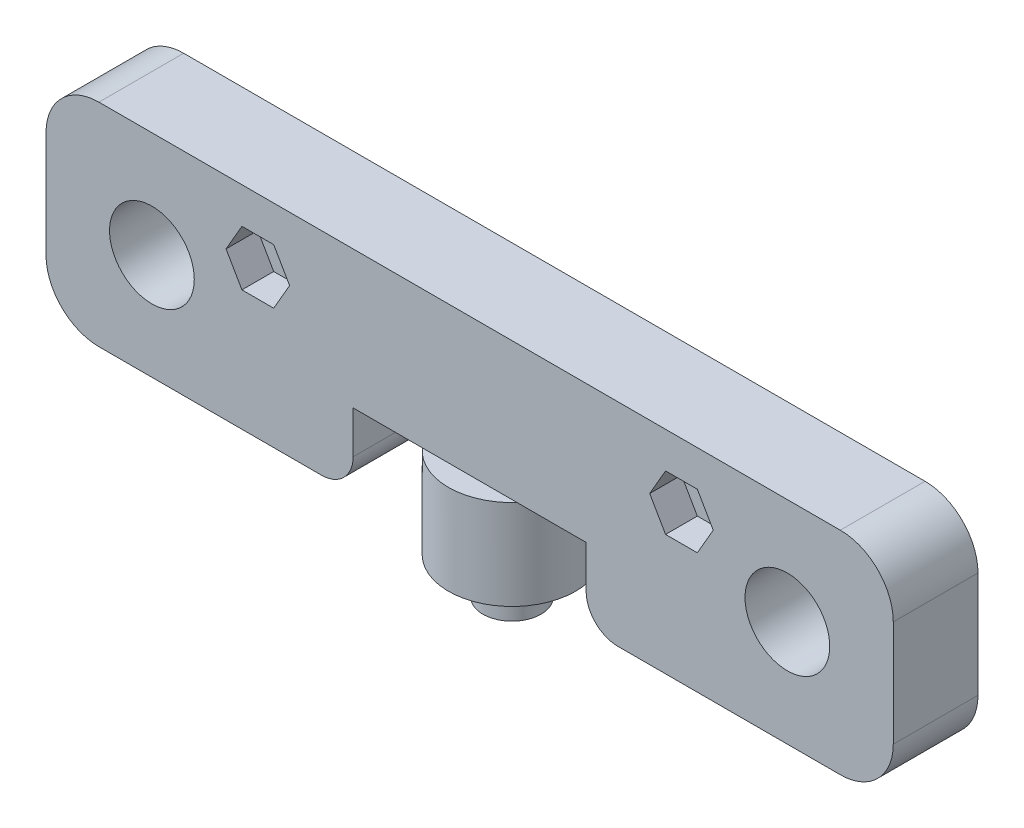
SolidWorks part; units mm, degrees
ref_plane "Front Plane" through (0, 0, 0) normal (0, 0, 1) x (1, 0, 0)
ref_plane "Top Plane" through (0, 0, 0) normal (0, 1, 0) x (1, 0, 0)
ref_plane "Right Plane" through (0, 0, 0) normal (1, 0, 0) x (0, 0, -1)
sketch "Sketch1" plane through (0, 0, 0) normal (0, 0, 1) x (1, 0, 0)
  line L0 (-11, -3) -> (-11, -10)
  line L1 (-11, -10) -> (-40, -10)
  line L2 (-40, -10) -> (-40, 10)
  line L3 (0, -12.103) -> (0, 12.103) construction
  line L4 (40, -10) -> (40, 10)
  line L5 (11, -10) -> (40, -10)
  line L6 (11, -3) -> (11, -10)
  line L7 (-11, -3) -> (11, -3)
  line L8 (-40, 10) -> (40, 10)
  circle A0 centre (-30, 0) radius 4
  circle A1 centre (-20, 4) radius 1.4
  circle A2 centre (20, 4) radius 1.4
  circle A3 centre (30, 0) radius 4
  dimension "D1" = 2.8
  dimension "D2" = 8
  dimension "D3" = 20
  dimension "D4" = 7
  dimension "D5" = 80
  dimension "D6" = 60
  dimension "D7" = 40
  dimension "D8" = 14
  dimension "D9" = 10
  dimension "D10" = 22
extrude "Boss-Extrude1" add sketch "Sketch1" along normal blind 8
fillet "outside curves" radius 5 4 edges at (40, -10, 4) (40, 10, 4) (-40, -10, 4) (-40, 10, 4)
fillet "inside curves" radius 3 2 edges at (11, -10, 4) (-11, -10, 4)
sketch "Sketch2" plane through (0, 0, 8) normal (0, 0, 1) x (1, 0, 0)
  line L0 (0, -4.4) -> (0, 4.4) construction
  line L1 (-17, 4) -> (-18.5, 6.5981)
  line L2 (-18.5, 6.5981) -> (-21.5, 6.5981)
  line L3 (-21.5, 6.5981) -> (-23, 4)
  line L4 (-23, 4) -> (-21.5, 1.4019)
  line L5 (-21.5, 1.4019) -> (-18.5, 1.4019)
  line L6 (-18.5, 1.4019) -> (-17, 4)
  line L7 (18.5, 1.4019) -> (17, 4)
  line L8 (21.5, 1.4019) -> (18.5, 1.4019)
  line L9 (23, 4) -> (21.5, 1.4019)
  line L10 (21.5, 6.5981) -> (23, 4)
  line L11 (18.5, 6.5981) -> (21.5, 6.5981)
  line L12 (17, 4) -> (18.5, 6.5981)
  circle A0 centre (-20, 4) radius 3 construction
  circle A1 centre (20, 4) radius 3 construction
  dimension "D1" = 6
extrude "bolt holes" cut sketch "Sketch2" against normal blind 3
sketch "Sketch3" plane through (0, -3, 0) normal (0, -1, 0) x (1, 0, 0)
  line L0 (-11, 8) -> (11, 0) construction
  line L1 (-11, 0) -> (11, 8) construction
  circle A0 centre (0, 4) radius 1.4
  dimension "D1" = 2.8
extrude "bearing screw hole" cut sketch "Sketch3" against normal blind 10
sketch "table" plane through (0, 0, 0) normal (0, 0, 1) x (1, 0, 0)
  line L0 (-25.0601, -65) -> (16.9388, -65)
  dimension "D1" = 65
sketch "Sketch5" plane through (0, -3, 0) normal (0, -1, 0) x (1, 0, 0)
  circle A0 centre (0, 4) radius 6
  circle A1 centre (0, 4) radius 1.4 construction
  dimension "D1" = 12
extrude "bearings" add sketch "Sketch5" along normal blind 8.5 contours A0
sketch "Sketch6" plane through (0, -11.5, 0) normal (0, -1, 0) x (1, 0, 0)
  circle A0 centre (0, 4) radius 2.75
  circle A1 centre (0, 4) radius 6 construction
  dimension "D1" = 5.5
extrude "screw" add sketch "Sketch6" along normal blind 3.5
